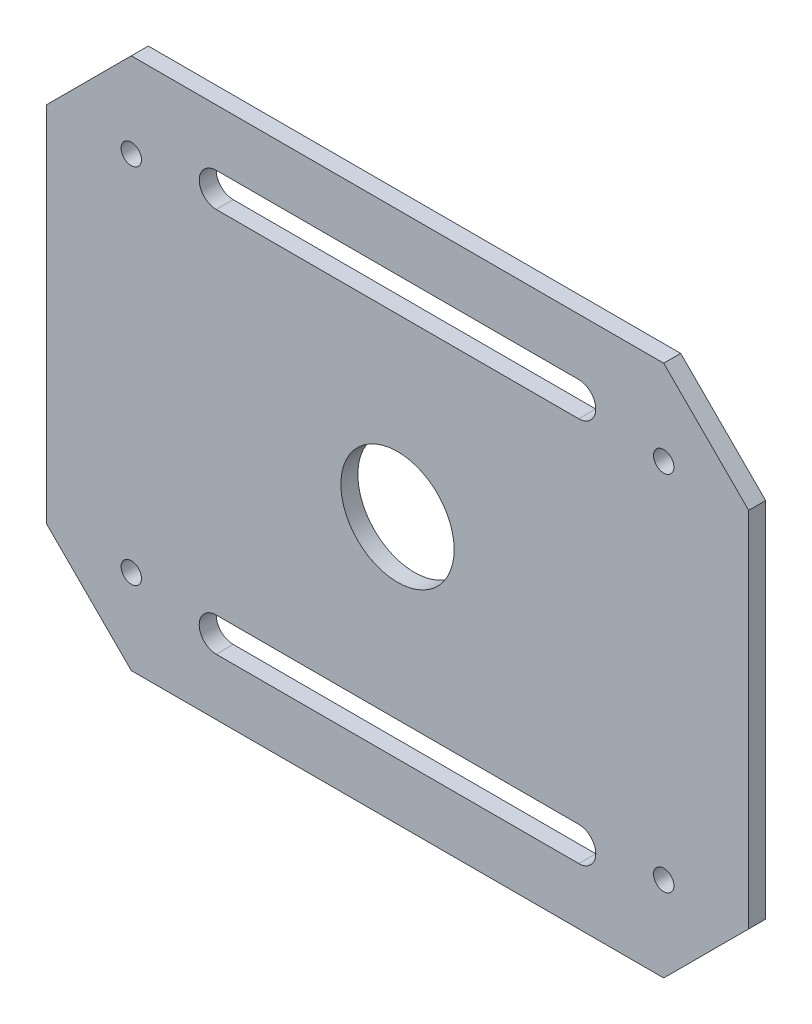
SolidWorks part; units mm, degrees
ref_plane "Front Plane" through (0, 0, 0) normal (0, 0, 1) x (1, 0, 0)
ref_plane "Top Plane" through (0, 0, 0) normal (0, 1, 0) x (1, 0, 0)
ref_plane "Right Plane" through (0, 0, 0) normal (1, 0, 0) x (0, 0, -1)
sketch "Sketch1" plane through (0, 0, 0) normal (0, 0, 1) x (1, 0, 0)
  line L0 (-39.9574, -43.5446) -> (-24.9574, -28.5446)
  line L1 (-24.9574, -28.5446) -> (69.0426, -28.5446)
  line L2 (69.0426, -28.5446) -> (84.0426, -43.5446)
  line L3 (-39.9574, -107.5446) -> (-24.9574, -122.5446)
  line L4 (-24.9574, -122.5446) -> (69.0426, -122.5446)
  line L5 (69.0426, -122.5446) -> (84.0426, -107.5446)
  line L6 (-39.9574, -43.5446) -> (-39.9574, -107.5446)
  line L15 (84.0426, -43.5446) -> (84.0426, -107.5446)
  line L16 (-24.9574, -43.5446) -> (69.0426, -43.5446) construction
  line L17 (69.0426, -43.5446) -> (69.0426, -107.5446) construction
  line L18 (69.0426, -107.5446) -> (-24.9574, -107.5446) construction
  line L19 (-24.9574, -107.5446) -> (-24.9574, -43.5446) construction
  line L20 (-39.9574, -43.5446) -> (-24.9574, -43.5446) construction
  line L21 (-24.9574, -43.5446) -> (-24.9574, -28.5446) construction
  line L22 (69.0426, -28.5446) -> (69.0426, -43.5446) construction
  line L23 (69.0426, -43.5446) -> (84.0426, -43.5446) construction
  line L24 (-39.9574, -107.5446) -> (-24.9574, -107.5446) construction
  line L25 (-24.9574, -107.5446) -> (-24.9574, -122.5446) construction
  line L26 (69.0426, -107.5446) -> (84.0426, -107.5446) construction
  line L27 (69.0426, -107.5446) -> (69.0426, -122.5446) construction
  line L28 (22.0426, -75.5446) -> (22.0426, -43.5446) construction
  line L29 (22.0426, -75.5446) -> (22.0426, -107.5446) construction
  line L30 (22.0426, -75.5446) -> (-24.9574, -75.5446) construction
  line L31 (22.0426, -75.5446) -> (69.0426, -75.5446) construction
  line L32 (-9.9574, -38.5446) -> (54.0426, -38.5446)
  line L33 (-9.9574, -44.5446) -> (54.0426, -44.5446)
  line L34 (-9.9574, -38.5446) -> (-9.9574, -44.5446) construction
  line L35 (54.0426, -38.5446) -> (54.0426, -44.5446) construction
  line L36 (-9.9574, -41.5446) -> (-24.9574, -41.5446) construction
  line L37 (54.0426, -41.5446) -> (69.0426, -41.5446) construction
  line L38 (-9.9657, -106.5446) -> (54.0509, -106.5446)
  line L39 (54.0509, -106.5446) -> (54.0509, -112.5446) construction
  line L40 (54.0509, -112.5446) -> (-9.9657, -112.5446)
  line L41 (-9.9657, -112.5446) -> (-9.9657, -106.5446) construction
  line L42 (-9.9657, -109.5446) -> (-24.9657, -109.5446) construction
  line L43 (54.0509, -109.5446) -> (69.0509, -109.5446) construction
  line L44 (22.0426, -112.5446) -> (22.0426, -122.5446) construction
  line L45 (22.0426, -38.5446) -> (22.0426, -28.5446) construction
  circle A8 centre (-24.9574, -43.5446) radius 1.8
  circle A9 centre (69.0426, -43.5446) radius 1.8
  circle A10 centre (69.0426, -107.5446) radius 1.8
  circle A11 centre (-24.9574, -107.5446) radius 1.8
  circle A12 centre (22.0426, -75.5446) radius 10
  arc A13 (-9.9574, -38.5446) -> (-9.9574, -44.5446) centre (-9.9574, -41.5446) ccw
  arc A14 (54.0426, -44.5446) -> (54.0426, -38.5446) centre (54.0426, -41.5446) ccw
  arc A15 (-9.9657, -106.5446) -> (-9.9657, -112.5446) centre (-9.9657, -109.5446) ccw
  arc A16 (54.0509, -112.5446) -> (54.0509, -106.5446) centre (54.0509, -109.5446) ccw
  dimension "D1" = 94
  dimension "D4" = 10
  dimension "D2" = 64
  dimension "D3" = 15
  dimension "D5" = 15
  dimension "D6" = 6
extrude "Boss-Extrude1" add sketch "Sketch1" along normal blind 3
